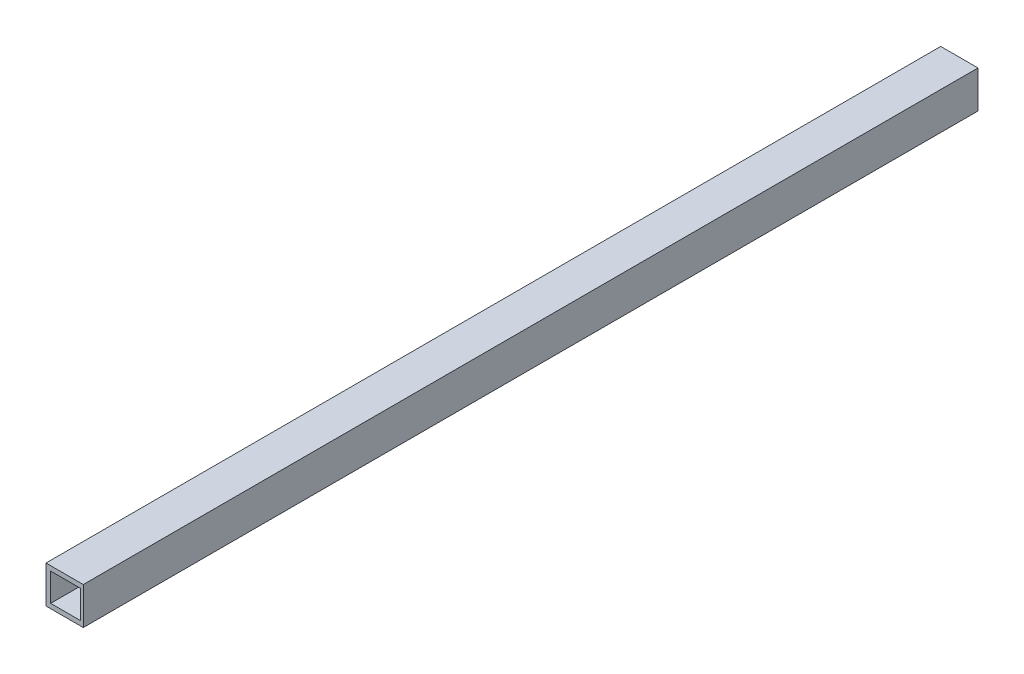
SolidWorks part; units mm, degrees
ref_plane "Front Plane" through (0, 0, 0) normal (0, 0, 1) x (1, 0, 0)
ref_plane "Top Plane" through (0, 0, 0) normal (0, 1, 0) x (1, 0, 0)
ref_plane "Right Plane" through (0, 0, 0) normal (1, 0, 0) x (0, 0, -1)
sketch "Sketch1" plane through (0, 0, 0) normal (0, 0, 1) x (1, 0, 0)
  line L1 (0, 0) -> (25.4, 0)
  line L2 (0, 0) -> (0, 25.4)
  line L3 (0, 25.4) -> (25.4, 25.4)
  line L4 (25.4, 0) -> (25.4, 25.4)
  dimension "D1" = 25.4
  dimension "D2" = 25.4
extrude "Boss-Extrude2" add sketch "Sketch1" along normal blind 609.6 contours L3 L4 L1 L2
sketch "Sketch2" plane through (0, 0, 0) normal (0, 0, -1) x (-1, 0, 0)
  line L0 (-23.4778, 22.225) -> (-3.175, 22.225)
  line L1 (-23.4778, 22.225) -> (-23.4778, 3.175)
  line L2 (-23.4778, 3.175) -> (-3.175, 3.175)
  line L3 (-3.175, 22.225) -> (-3.175, 3.175)
  line L4 (0, 0) -> (0, 25.4) construction
  line L5 (0, 0) -> (-25.4, 0) construction
  dimension "D1" = 3.175
  dimension "D2" = 3.175
extrude "Cut-Extrude1" cut sketch "Sketch2" against normal through all
